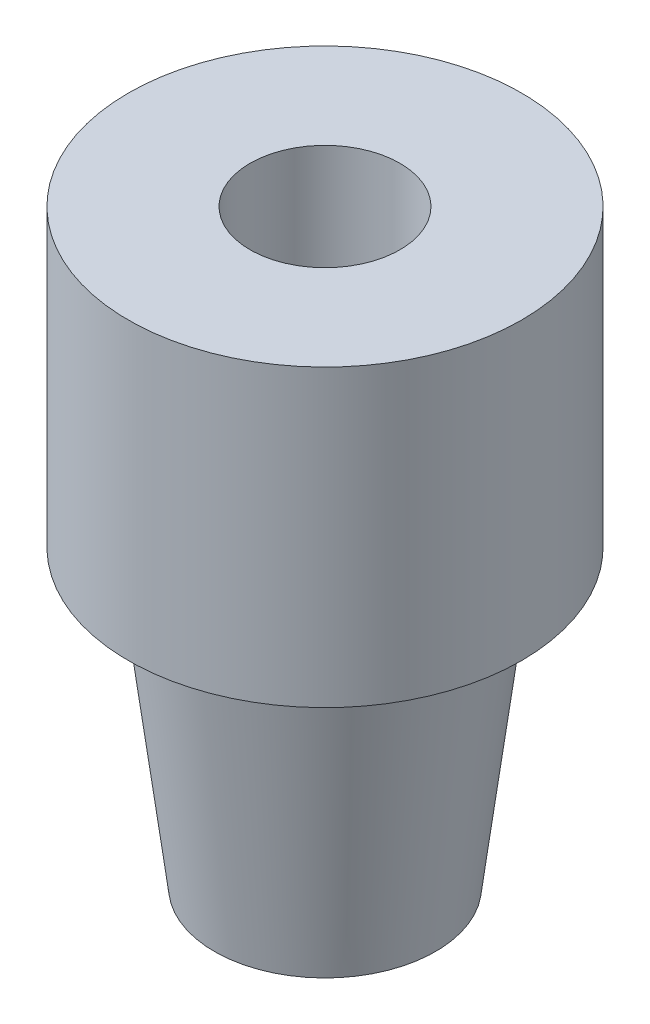
SolidWorks part; units mm, degrees
ref_plane "Alzado" through (0, 0, 0) normal (0, 0, 1) x (1, 0, 0)
ref_plane "Planta" through (0, 0, 0) normal (0, 1, 0) x (1, 0, 0)
ref_plane "Vista lateral" through (0, 0, 0) normal (1, 0, 0) x (0, 0, -1)
sketch "Croquis1" plane through (0, 0, 0) normal (0, 0, 1) x (1, 0, 0)
  line L0 (0, 12.5016) -> (0, -15.7339) construction
  line L1 (0, 8.2661) -> (8, 8.2661)
  line L2 (8, 8.2661) -> (8, -3.7339)
  line L3 (8, -3.7339) -> (6, -3.7339)
  line L4 (6, -3.7339) -> (4.5, -15.7339)
  line L5 (4.5, -15.7339) -> (0, -15.7339)
  line L6 (0, -15.7339) -> (0, 8.2661)
  dimension "D1" = 8
  dimension "D2" = 12
  dimension "D3" = 12
  dimension "D4" = 6
  dimension "D5" = 4.5
revolve "Revolución1" add sketch "Croquis1" angle 360 about L0
sketch "Croquis2" plane through (0, 8.2661, 0) normal (0, 1, 0) x (1, 0, 0)
  circle A0 centre (0, 0) radius 3.05
  dimension "D1" = 6.1
extrude "Cortar-Extruir1" cut sketch "Croquis2" against normal blind 10
